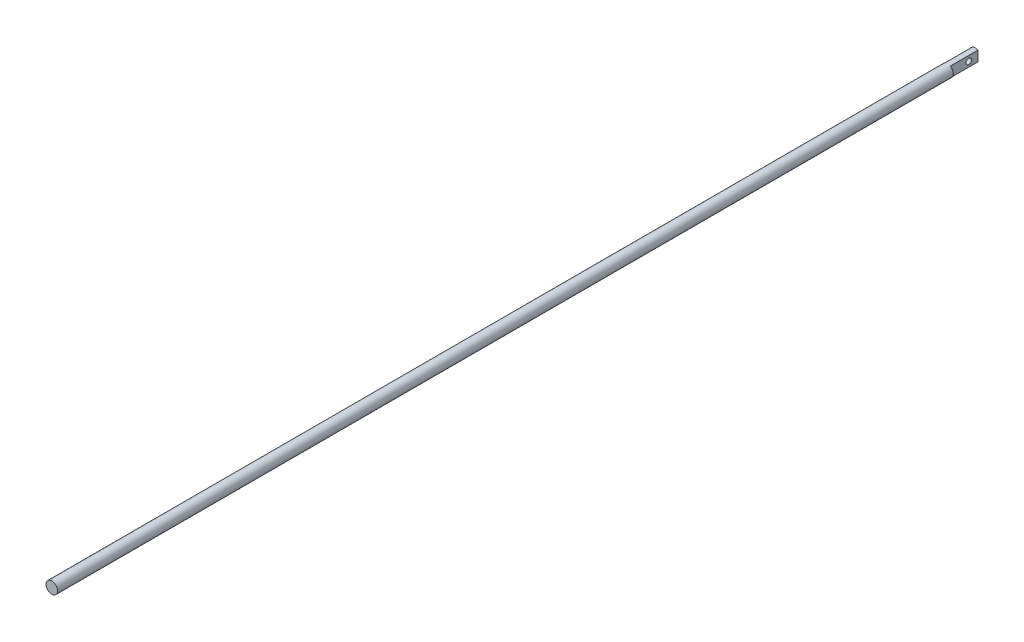
SolidWorks part; units mm, degrees
ref_plane "Front Plane" through (0, 0, 0) normal (0, 0, 1) x (1, 0, 0)
ref_plane "Top Plane" through (0, 0, 0) normal (0, 1, 0) x (1, 0, 0)
ref_plane "Right Plane" through (0, 0, 0) normal (1, 0, 0) x (0, 0, -1)
sketch "Sketch1" plane through (0, 0, 0) normal (0, 0, 1) x (1, 0, 0)
  circle A0 centre (0, 0) radius 1.5875
  dimension "D1" = 3.175
extrude "Boss-Extrude1" add sketch "Sketch1" along normal blind 254
sketch "Sketch2" plane through (0, 0, 0) normal (0, 1, 0) x (1, 0, 0)
  line L0 (1.5875, -254) -> (1.5875, 0) construction
  line L1 (0.762, 0) -> (1.5875, 0)
  line L2 (0.762, 0) -> (0.762, -7.62)
  line L3 (0.762, -7.62) -> (1.5875, -7.62)
  line L4 (1.5875, 0) -> (1.5875, -7.62)
  line L6 (-0.762, 0) -> (-1.5875, 0)
  line L7 (-0.762, 0) -> (-0.762, -7.62)
  line L8 (-0.762, -7.62) -> (-1.5875, -7.62)
  line L9 (-1.5875, 0) -> (-1.5875, -7.62)
  dimension "D1" = 3.175
  dimension "D2" = 1.524
  dimension "D3" = 7.62
extrude "Cut-Extrude1" cut sketch "Sketch2" against normal through all and the other way through all
sketch "Sketch3" plane through (0, 0, 0) normal (1, 0, 0) x (0, 0, -1)
  circle A0 centre (-2.54, 0) radius 0.762
  dimension "D1" = 1.524
  dimension "D2" = 2.54
extrude "Cut-Extrude2" cut sketch "Sketch3" against normal up to next and the other way up to next
